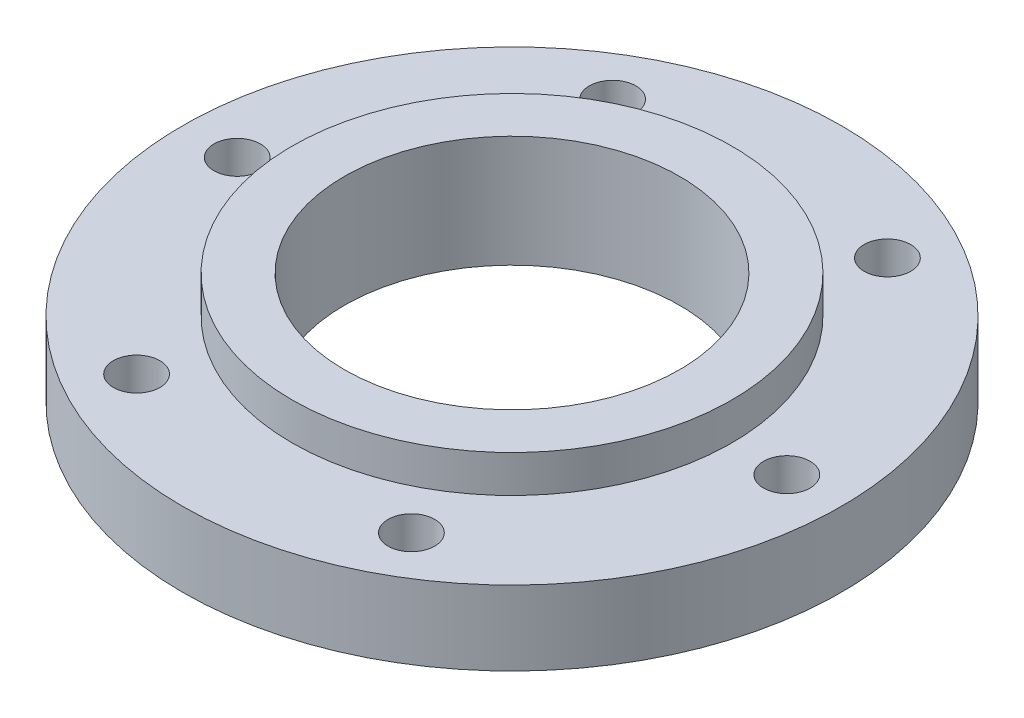
SolidWorks part; units mm, degrees
ref_plane "Front Plane" through (0, 0, 0) normal (0, 0, 1) x (1, 0, 0)
ref_plane "Top Plane" through (0, 0, 0) normal (0, 1, 0) x (1, 0, 0)
ref_plane "Right Plane" through (0, 0, 0) normal (1, 0, 0) x (0, 0, -1)
sketch "Sketch1" plane through (0, 0, 0) normal (0, 1, 0) x (1, 0, 0)
  circle A0 centre (0, 0) radius 22.479
  circle A1 centre (0, 0) radius 11.43
  dimension "D1" = 44.958
  dimension "D2" = 22.86
extrude "Boss-Extrude1" add sketch "Sketch1" along normal blind 5.08
sketch "Sketch2" plane through (0, 5.08, 0) normal (0, 1, 0) x (1, 0, 0)
  circle A0 centre (0, 0) radius 14.9987
  circle A1 centre (0, 0) radius 11.43
  dimension "D1" = 29.9974
extrude "Boss-Extrude2" add sketch "Sketch2" along normal blind 2.54
sketch "Sketch3" plane through (0, 5.08, 0) normal (0, 1, 0) x (1, 0, 0)
  circle A0 centre (-18.7454, 0) radius 1.5875
  circle A1 centre (-9.3727, 16.234) radius 1.5875
  circle A2 centre (9.3727, 16.234) radius 1.5875
  circle A3 centre (18.7454, 0) radius 1.5875
  circle A4 centre (9.3727, -16.234) radius 1.5875
  circle A5 centre (-9.3727, -16.234) radius 1.5875
  point P14 (0, 0)
  dimension "D1" = 3.175
  dimension "D2" = 6
extrude "Cut-Extrude1" cut sketch "Sketch3" against normal through all
